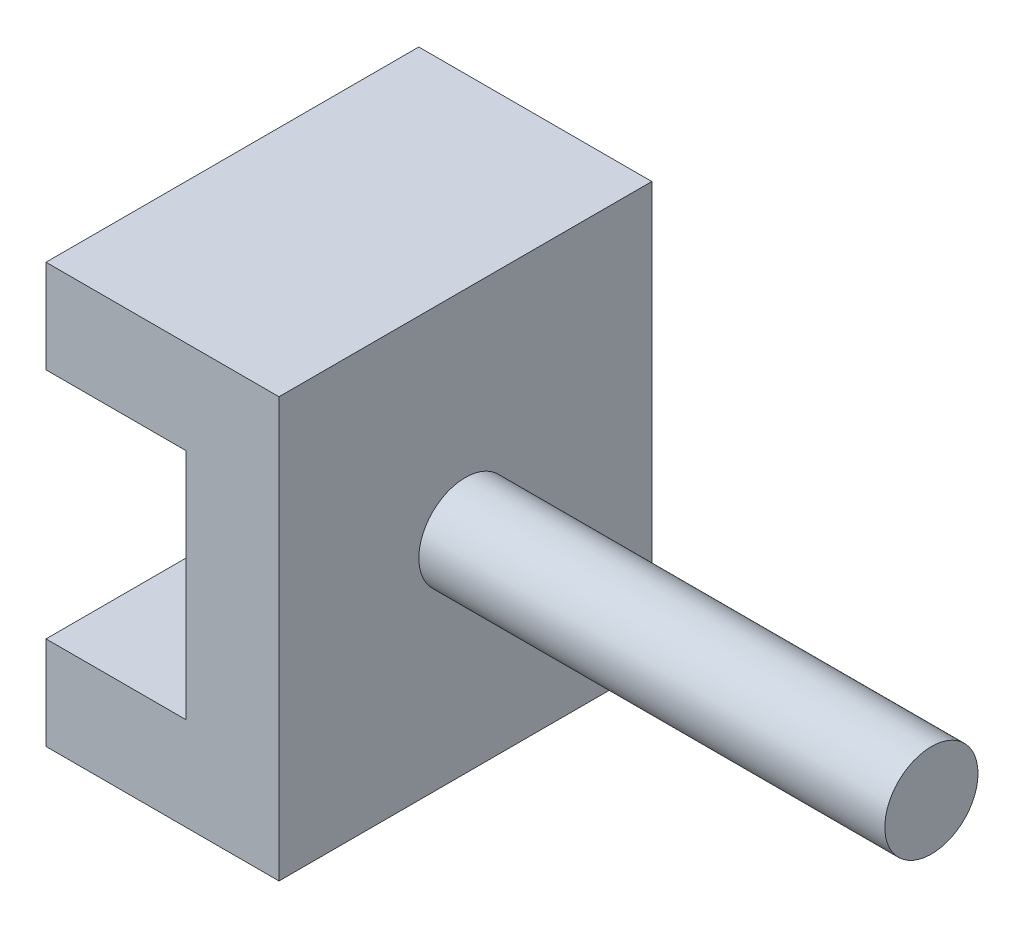
SolidWorks part; units mm, degrees
ref_plane "Front Plane" through (0, 0, 0) normal (0, 0, 1) x (1, 0, 0)
ref_plane "Top Plane" through (0, 0, 0) normal (0, 1, 0) x (1, 0, 0)
ref_plane "Right Plane" through (0, 0, 0) normal (1, 0, 0) x (0, 0, -1)
sketch "Sketch1" plane through (0, 0, 0) normal (0, 0, 1) x (1, 0, 0)
  line L0 (0, 10) -> (0, 35)
  line L5 (0, 0) -> (-25, 0)
  line L10 (0, 0) -> (0, 10)
  line L11 (-10, 10) -> (-25, 10)
  line L12 (-25, 0) -> (-25, 10)
  line L13 (-10, 35) -> (-10, 10)
  line L15 (-10, 35) -> (-25, 35)
  line L16 (0, 35) -> (0, 45)
  line L17 (0, 45) -> (-25, 45)
  line L18 (-25, 35) -> (-25, 45)
  dimension "D1" = 10
  dimension "D2" = 25
  dimension "D3" = 25
  dimension "D4" = 25
  dimension "D5" = 10
  dimension "D6" = 10
  dimension "D7" = 25
  dimension "D8" = 15
extrude "Boss-Extrude1" add sketch "Sketch1" along normal blind 40
sketch "Sketch2" plane through (0, 0, 0) normal (1, 0, 0) x (0, 0, -1)
  line L0 (-40, 0) -> (0, 45) construction
  line L1 (-40, 45) -> (0, 0) construction
  line L4 (0, 0) -> (0, 45)
  line L5 (0, 45) -> (-40, 45)
  line L6 (-40, 45) -> (-40, 0)
  line L7 (-40, 0) -> (0, 0)
  line L8 (0, 0) -> (0, 45)
  line L9 (0, 45) -> (-40, 45)
  line L10 (-40, 45) -> (-40, 0)
  line L11 (-40, 0) -> (0, 0)
  circle A0 centre (-20, 22.5) radius 5
  dimension "3" = 10
  dimension "D1" = 0
extrude "Boss-Extrude2" add sketch "Sketch2" along normal blind 50 contours A0
ref_plane "Plane3" through (10, 0, 0) normal (1, 0, 0) x (0, 0, -1)
sketch "Sketch10" plane through (10, 0, 0) normal (1, 0, 0) x (0, 0, -1)
  circle A1 centre (-20, 22.5) radius 5
  circle A2 centre (-20, 22.5) radius 5
  dimension "D1" = 0
ref_plane "Plane4" through (0, 0, 20) normal (0, 0, 1) x (1, 0, 0)
sketch "Sketch12" plane through (0, 0, 20) normal (0, 0, 1) x (1, 0, 0)
  line L0 (50, 27.5) -> (0, 27.5) construction
  line L1 (10.6667, 27.5) -> (9.3333, 27.5)
  line L2 (10.6667, 27.5) -> (10.6667, 29.5)
  line L3 (10.6667, 29.5) -> (9.3333, 29.5)
  line L4 (9.3333, 27.5) -> (9.3333, 29.5)
  line L5 (0, 0) -> (0, 45) construction
  point P6 (0, 0)
  point P7 (10, 27.5)
  dimension "D1" = 2
  dimension "D2" = 1.3333
  dimension "D3" = 10
